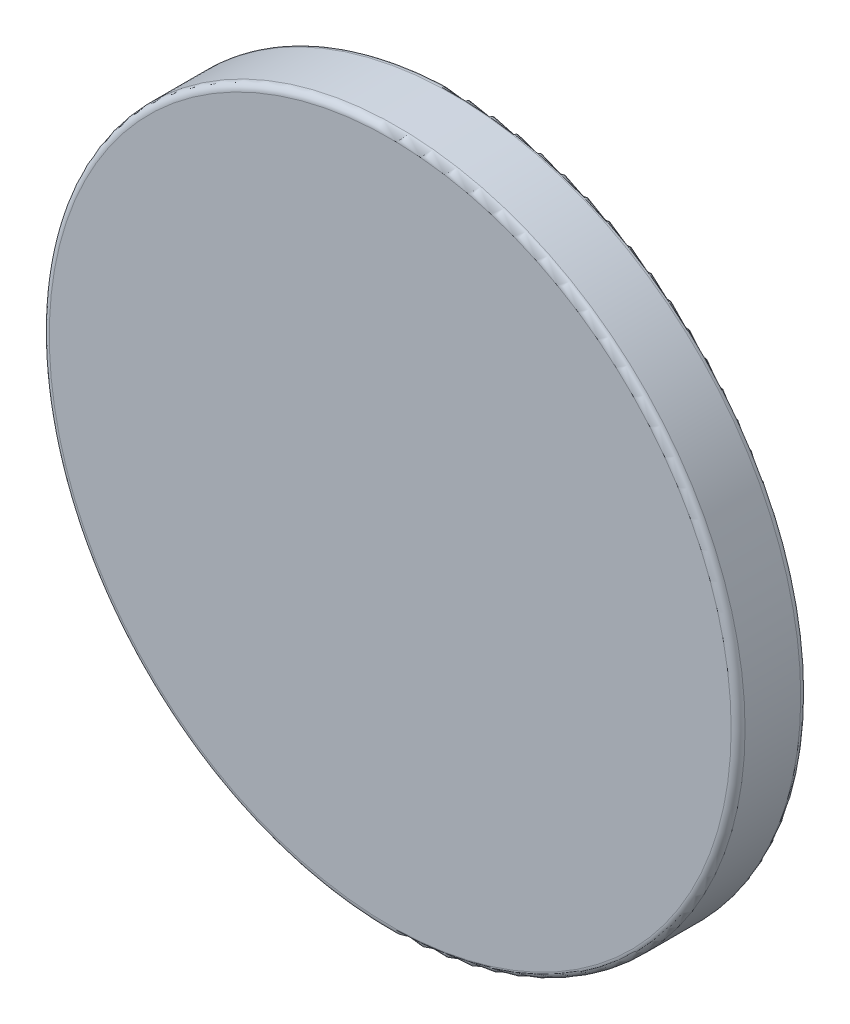
SolidWorks part; units mm, degrees
ref_plane "Front Plane" through (0, 0, 0) normal (0, 0, 1) x (1, 0, 0)
ref_plane "Top Plane" through (0, 0, 0) normal (0, 1, 0) x (1, 0, 0)
ref_plane "Right Plane" through (0, 0, 0) normal (1, 0, 0) x (0, 0, -1)
sketch "Sketch1" plane through (0, 0, 0) normal (0, 0, 1) x (1, 0, 0)
  circle A0 centre (0, 0) radius 50
  dimension "D1" = 100
extrude "Boss-Extrude1" add sketch "Sketch1" along normal blind 10
fillet "Fillet1" radius 1 2 edges at (50, 0, 0) (50, 0, 10)
